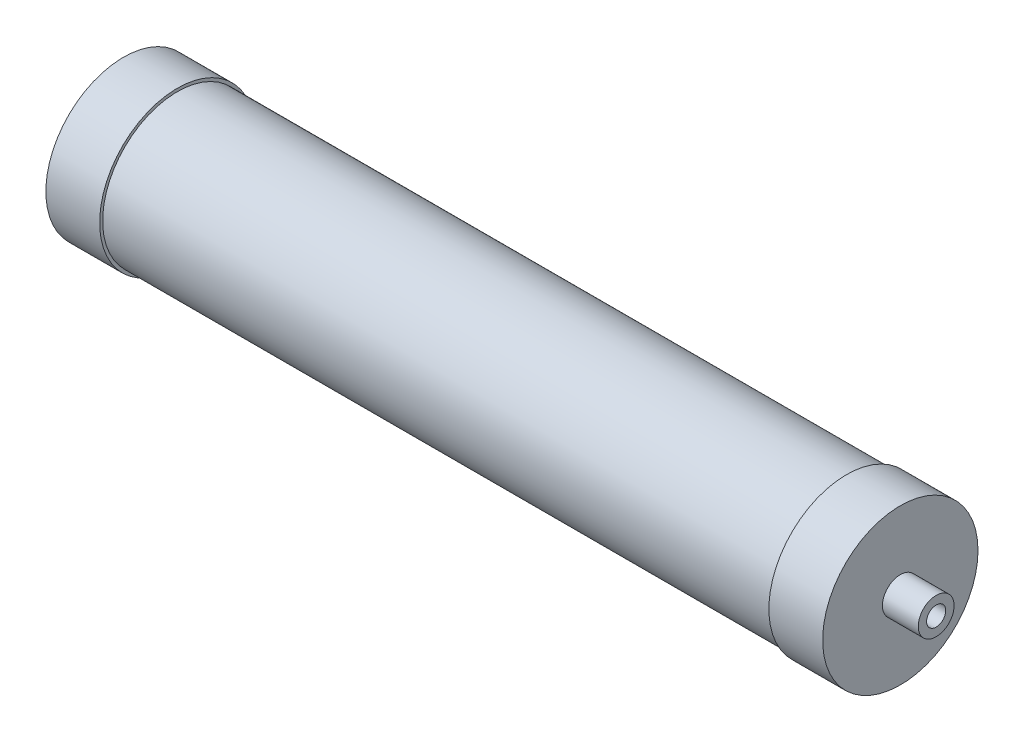
SolidWorks part; units mm, degrees
ref_plane "Front Plane" through (0, 0, 0) normal (0, 0, 1) x (1, 0, 0)
ref_plane "Top Plane" through (0, 0, 0) normal (0, 1, 0) x (1, 0, 0)
ref_plane "Right Plane" through (0, 0, 0) normal (1, 0, 0) x (0, 0, -1)
other "Configuration Table"
sketch "Sketch1" plane through (0, 0, 0) normal (1, 0, 0) x (0, 0, -1)
  circle A0 centre (0, 0) radius 25
  dimension "D1" = 50
extrude "Body" add sketch "Sketch1" along normal blind 260 from offset 130
sketch "Sketch2" plane through (0, 0, 0) normal (1, 0, 0) x (0, 0, -1)
  circle A0 centre (0, 0) radius 26
  dimension "D1" = 52
extrude "End_Cap_In" add sketch "Sketch2" along normal blind 18 from offset 130
sketch "Sketch3" plane through (0, 0, 0) normal (1, 0, 0) x (0, 0, -1)
  circle A0 centre (0, 0) radius 26
  dimension "D1" = 52
extrude "End_Cap_Out" add sketch "Sketch3" along normal blind 18 from offset 112
sketch "Sketch4" plane through (0, 0, 0) normal (1, 0, 0) x (0, 0, -1)
  circle A0 centre (0, 0) radius 6
  dimension "D1" = 12
extrude "Inlet_Port" add sketch "Sketch4" along normal blind 12 from offset 142
sketch "Sketch5" plane through (0, 0, 0) normal (1, 0, 0) x (0, 0, -1)
  circle A0 centre (0, 0) radius 3.2
  dimension "D1" = 6.4
extrude "Inlet_Socket" cut sketch "Sketch5" along normal blind 10 from offset 142
sketch "Sketch6" plane through (0, 0, 0) normal (1, 0, 0) x (0, 0, -1)
  circle A0 centre (0, 0) radius 6
  dimension "D1" = 12
extrude "Outlet_Port" add sketch "Sketch6" along normal blind 12 from offset 130
sketch "Sketch7" plane through (0, 0, 0) normal (1, 0, 0) x (0, 0, -1)
  circle A0 centre (0, 0) radius 3.2
  dimension "D1" = 6.4
extrude "Outlet_Socket" cut sketch "Sketch7" against normal blind 10 from offset 142
equation "\"Jar_OD\"= 90  'ASSUMED - Part G fallback - jar outer diameter"
equation "\"Jar_H\"= 120  'ASSUMED - Part G fallback - jar height"
equation "\"Pump_L\"= 45  'ASSUMED - Part G fallback"
equation "\"Pump_W\"= 24  'ASSUMED - Part G fallback"
equation "\"Pump_H\"= 33  'ASSUMED - Part G fallback"
equation "\"Pump_Outlet_OD\"= 7.5  'ASSUMED - Part G fallback"
equation "\"Tube_OD\"= 8  'ASSUMED - Part G fallback"
equation "\"Tube_ID\"= 6  'ASSUMED - Part G fallback"
equation "\"TDS_Body_Dia\"= 12  'ASSUMED - Part G fallback"
equation "\"TDS_Wet_Len\"= 45  'ASSUMED - Part G fallback - length in water"
equation "\"DS_Tube_Dia\"= 6  'ASSUMED - Part G fallback"
equation "\"DS_Tube_Len\"= 50  'ASSUMED - Part G fallback"
equation "\"ORP_Body_Dia\"= 12  'ASSUMED - Part G fallback"
equation "\"ORP_Body_Len\"= 150  'ASSUMED - Part G fallback"
equation "\"ORP_Cap_Dia\"= 16  'ASSUMED - Part G fallback"
equation "\"Turb_W\"= 33  'ASSUMED - Part G fallback - head width"
equation "\"Turb_D\"= 28  'ASSUMED - Part G fallback - head depth"
equation "\"Turb_H\"= 30  'ASSUMED - Part G fallback - head height"
equation "\"Turb_Slot_W\"= 10  'ASSUMED - Part G fallback - slot width"
equation "\"Flow_L\"= 62  'ASSUMED - Part G fallback YF-S201"
equation "\"Flow_W\"= 36  'ASSUMED - Part G fallback"
equation "\"Flow_H\"= 35  'ASSUMED - Part G fallback"
equation "\"Thread_G12_OD\"= 20.955  'ASSUMED - Part G fallback thread G1/2 (major diameter)"
equation "\"Valve_L\"= 75  'ASSUMED - Part G fallback"
equation "\"Valve_W\"= 45  'ASSUMED - Part G fallback"
equation "\"Valve_H\"= 60  'ASSUMED - Part G fallback"
equation "\"Tee_L\"= 40  'ASSUMED - Part G fallback - overall length"
equation "\"Tee_Branch_L\"= 25  'ASSUMED - Part G fallback"
equation "\"Tee_OD\"= 12  'ASSUMED - Part G fallback"
equation "\"LED_Board_L\"= 20  'ASSUMED - Part G fallback"
equation "\"LED_Board_W\"= 20  'ASSUMED - Part G fallback - LED at centre"
equation "\"GUVA_L\"= 20  'ASSUMED - Part G fallback"
equation "\"GUVA_W\"= 12  'ASSUMED - Part G fallback - sensor at centre"
equation "\"Reed_L\"= 27  'ASSUMED - Part G fallback MC-38 half"
equation "\"Reed_W\"= 14  'ASSUMED - Part G fallback"
equation "\"Reed_H\"= 8  'ASSUMED - Part G fallback"
equation "\"ESP_L\"= 51  'ASSUMED - Part G fallback"
equation "\"ESP_W\"= 28  'ASSUMED - Part G fallback"
equation "\"TFT_L\"= 58  'ASSUMED - Part G fallback - board"
equation "\"TFT_W\"= 35  'ASSUMED - Part G fallback - board"
equation "\"TFT_Win_L\"= 35  'ASSUMED - Part G fallback - visible window"
equation "\"TFT_Win_W\"= 28  'ASSUMED - Part G fallback - visible window"
equation "\"Relay_L\"= 50  'ASSUMED - Part G fallback"
equation "\"Relay_W\"= 26  'ASSUMED - Part G fallback"
equation "\"Relay_H\"= 19  'ASSUMED - Part G fallback"
equation "\"Mosfet_L\"= 34  'ASSUMED - Part G fallback"
equation "\"Mosfet_W\"= 17  'ASSUMED - Part G fallback"
equation "\"Mosfet_H\"= 12  'ASSUMED - Part G fallback"
equation "\"TDS_Board_L\"= 42  'ASSUMED - Part G fallback"
equation "\"TDS_Board_W\"= 32  'ASSUMED - Part G fallback"
equation "\"Turb_Board_L\"= 38  'ASSUMED - Part G fallback"
equation "\"Turb_Board_W\"= 28  'ASSUMED - Part G fallback"
equation "\"BNC_Thread_Dia\"= 9.5  'ASSUMED - Part G fallback"
equation "\"Plate_L\"= 420  'ASSUMED - Part G fallback"
equation "\"Plate_W\"= 297  'ASSUMED - Part G fallback"
equation "\"Plate_T\"= 6  'ASSUMED - Part G fallback"
equation "\"Booster_L\"= 150  'ASSUMED - Part G fallback - booster pump"
equation "\"Booster_W\"= 95  'ASSUMED - Part G fallback"
equation "\"Booster_H\"= 100  'ASSUMED - Part G fallback"
equation "\"PTube_OD\"= 6.35  'ASSUMED - Part G fallback - product tube 1/4 inch"
equation "\"Qz_Out\"= 12  'ASSUMED - Part G fallback - quartz channel outside square"
equation "\"Qz_Path\"= 10  'ASSUMED - Part G fallback - quartz channel inside light path"
equation "\"Qz_L\"= 40  'ASSUMED - Part G fallback - quartz channel length"
equation "\"LED860_Dia\"= 5  'ASSUMED - Part G fallback - 860 nm LED"
equation "\"BPW_L\"= 5.4  'ASSUMED - Part G fallback - BPW34"
equation "\"BPW_W\"= 4.3  'ASSUMED - Part G fallback - BPW34"
equation "\"Cart_Dia\"= 50  'ASSUMED - Part G fallback - sediment and pre-carbon cartridges"
equation "\"Cart_L\"= 255  'ASSUMED - Part G fallback"
equation "\"UF_Dia\"= 50  'ASSUMED - Part G fallback - UF cartridge"
equation "\"UF_L\"= 260  'ASSUMED - Part G fallback"
equation "\"RO_Dia\"= 62  'ASSUMED - Part G fallback - RO membrane housing"
equation "\"RO_L\"= 300  'ASSUMED - Part G fallback"
equation "\"UVC_Dia\"= 40  'ASSUMED - Part G fallback - UV-C chamber"
equation "\"UVC_L\"= 300  'ASSUMED - Part G fallback"
equation "\"Tank_W\"= 260  'ASSUMED - Part G fallback - storage tank"
equation "\"Tank_D\"= 160  'ASSUMED - Part G fallback"
equation "\"Tank_H\"= 300  'ASSUMED - Part G fallback"
equation "\"Cab_W\"= 400  'ASSUMED - Part G fallback - purifier cabinet"
equation "\"Cab_D\"= 270  'ASSUMED - Part G fallback"
equation "\"Cab_H\"= 560  'ASSUMED - Part G fallback"
equation "\"ORP_Board_L\"= 40  'ASSUMED - Part G fallback - ORP buffer board"
equation "\"ORP_Board_W\"= 30  'ASSUMED - Part G fallback"
equation "\"Opt_Board_L\"= 50  'ASSUMED - Part G fallback - optical front-end board"
equation "\"Opt_Board_W\"= 40  'ASSUMED - Part G fallback"
equation "\"Buck_L\"= 43  'ASSUMED - Part G fallback - 12 V to 5 V buck module"
equation "\"Buck_W\"= 21  'ASSUMED - Part G fallback"
equation "\"Buck_H\"= 14  'ASSUMED - Part G fallback"
equation "\"BB_L\"= 165  'ASSUMED - Part G fallback - breadboard (As_Built_R3 only)"
equation "\"BB_W\"= 55  'ASSUMED - Part G fallback"
equation "\"BB_H\"= 10  'ASSUMED - Part G fallback"
equation "\"Cuv_W\"= 12.5  'ASSUMED - old R3 cuvette (station suppressed in SS4)"
equation "\"Cuv_D\"= 12.5  'ASSUMED - old R3 cuvette (station suppressed in SS4)"
equation "\"Cuv_H\"= 45  'ASSUMED - old R3 cuvette (station suppressed in SS4)"
equation "\"Probe_Clr\"= 0.3  'DESIGN VALUE - Part C rule 3 - printed probe hole = diameter + 0.3"
equation "\"Label_H\"= 0.6  'DESIGN VALUE - Part D - raised label height"
